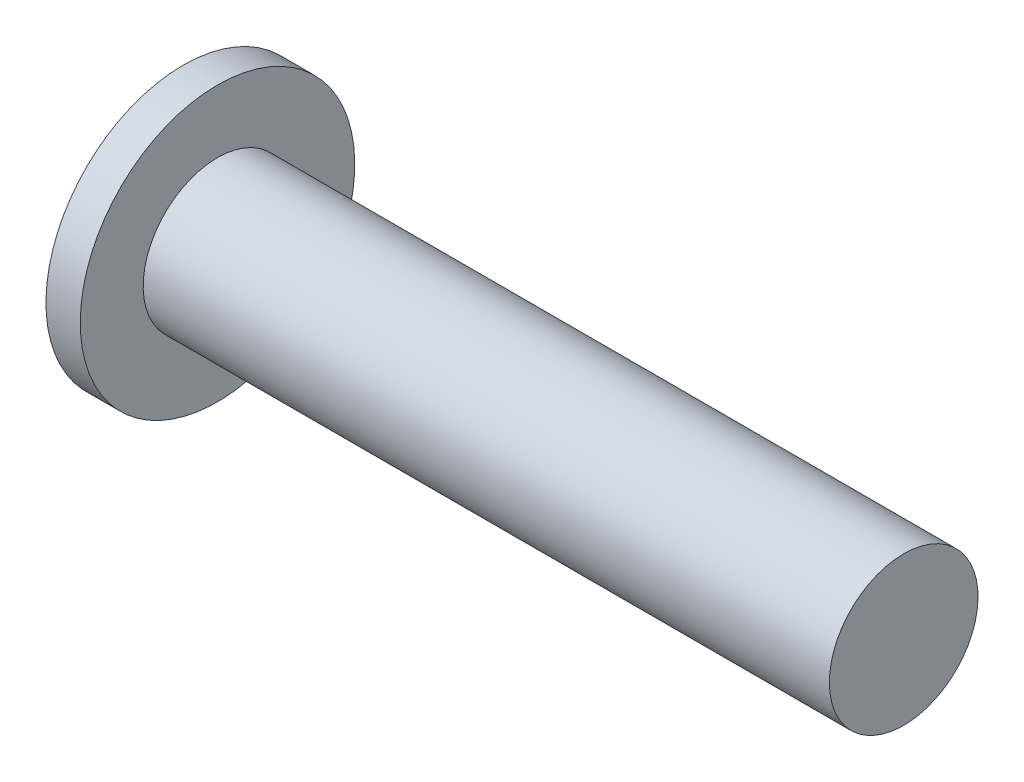
SolidWorks part; units mm, degrees
ref_plane "Alzado" through (0, 0, 0) normal (0, 0, 1) x (1, 0, 0)
ref_plane "Planta" through (0, 0, 0) normal (0, 1, 0) x (1, 0, 0)
ref_plane "Vista lateral" through (0, 0, 0) normal (1, 0, 0) x (0, 0, -1)
sketch "Croquis1" plane through (0, 0, 0) normal (0, 0, 1) x (1, 0, 0)
  line L0 (0, 0) -> (0, 6)
  line L1 (0, 6) -> (1.5, 6)
  line L2 (1.5, 6) -> (1.5, 3.25)
  line L3 (1.5, 3.25) -> (31.5, 3.25)
  line L4 (31.5, 3.25) -> (31.5, 0)
  line L5 (31.5, 0) -> (0, 0)
  dimension "D1" = 30
  dimension "D2" = 1.5
  dimension "D3" = 3.25
  dimension "D4" = 6
revolve "Revolución1" add sketch "Croquis1" angle 360 about L5
